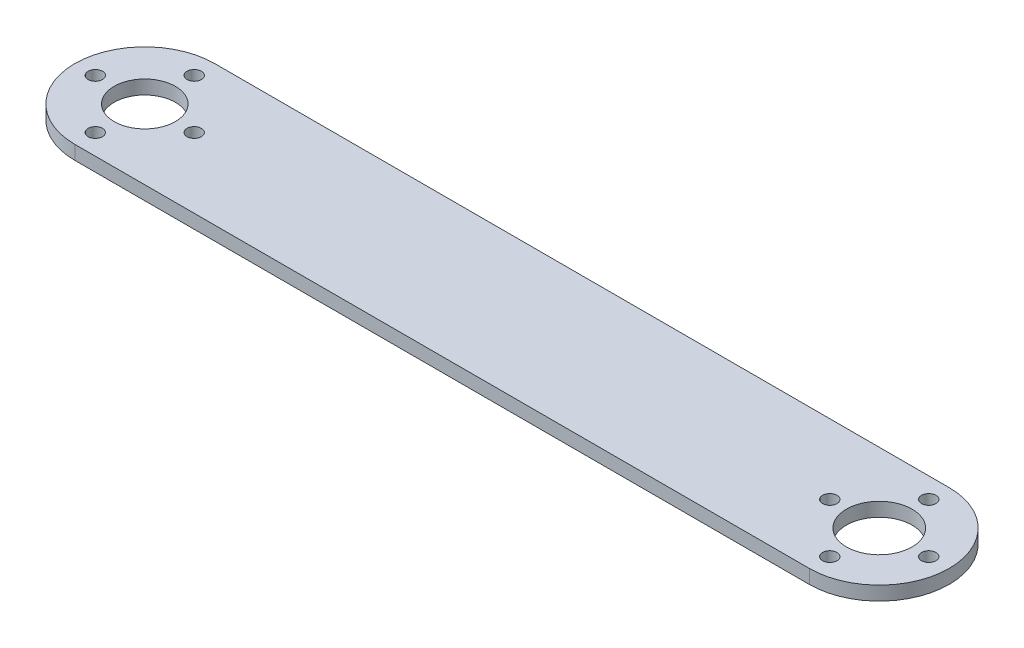
SolidWorks part; units mm, degrees
ref_plane "Front" through (0, 0, 0) normal (0, 0, 1) x (1, 0, 0)
ref_plane "Top" through (0, 0, 0) normal (0, 1, 0) x (1, 0, 0)
ref_plane "Right" through (0, 0, 0) normal (1, 0, 0) x (0, 0, -1)
sketch "Sketch1" plane through (0, 0, 0) normal (0, 1, 0) x (1, 0, 0)
  line L1 (0, 0) -> (168, 0)
  line L2 (0, 0) -> (0, 32)
  line L3 (0, 32) -> (168, 32)
  line L4 (168, 0) -> (168, 32)
  arc A0 (0, 32) -> (0, 0) centre (0, 16) ccw
  arc A1 (168, 32) -> (168, 0) centre (168, 16) cw
  circle A2 centre (0, 16) radius 7
  circle A3 centre (168, 16) radius 7.5
  dimension "D1" = 32
  dimension "D2" = 168
extrude "Boss-Extrude1" add sketch "Sketch1" along normal blind 3.175 contours A3 L4 L3 L2 A2 L1 | A2 L2 A0 | A3 L4 A1
sketch "Sketch2" plane through (0, 3.175, 0) normal (0, 1, 0) x (1, 0, 0)
  line L0 (84, 32) -> (84, 0)
  line L1 (0, 32) -> (168, 32) construction
  line L2 (0, 0) -> (168, 0) construction
  circle A0 centre (0, 16) radius 11.3137
  circle A1 centre (-11.3137, 16) radius 1.65
  circle A2 centre (11.3137, 16) radius 1.65
  circle A3 centre (0, 27.3137) radius 1.65
  circle A4 centre (0, 4.6863) radius 1.65
  circle A5 centre (168, 4.6863) radius 1.65
  circle A6 centre (156.6863, 16) radius 1.65
  circle A7 centre (179.3137, 16) radius 1.65
  circle A8 centre (168, 27.3137) radius 1.65
extrude "Cut-Extrude1" cut sketch "Sketch2" against normal blind 10 contours A6 | A8 | A1 | A3 | A2 | A4 | A5 | A7
